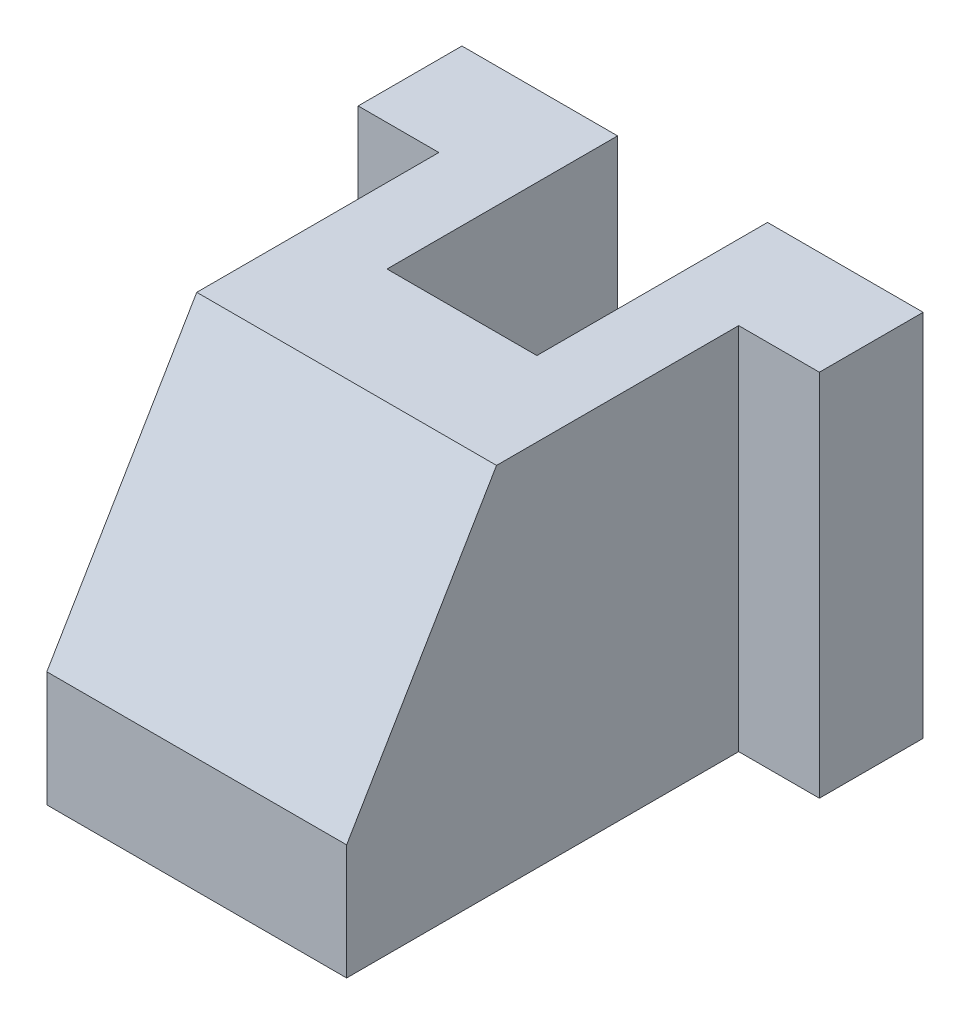
SolidWorks part; units mm, degrees
ref_plane "Front Plane" through (0, 0, 0) normal (0, 0, 1) x (1, 0, 0)
ref_plane "Top Plane" through (0, 0, 0) normal (0, 1, 0) x (1, 0, 0)
ref_plane "Right Plane" through (0, 0, 0) normal (1, 0, 0) x (0, 0, -1)
sketch "Sketch1" plane through (0, 0, 0) normal (1, 0, 0) x (0, 0, -1)
  line L0 (-43, 0) -> (0, 0)
  line L1 (0, 0) -> (0, 32)
  line L2 (0, 32) -> (-30, 32)
  line L3 (-30, 32) -> (-43, 10)
  line L4 (-43, 10) -> (-43, 0)
  dimension "D1" = 10
  dimension "D2" = 43
  dimension "D3" = 32
  dimension "D4" = 30
extrude "Boss-Extrude2" add sketch "Sketch1" against normal blind 26
sketch "Sketch2" plane through (0, 0, 0) normal (1, 0, 0) x (0, 0, -1)
  line L0 (0, 32) -> (-9, 32)
  line L1 (0, 32) -> (-30, 32) construction
  line L2 (-9, 32) -> (-9, 0)
  line L3 (-43, 0) -> (0, 0) construction
  line L4 (-9, 0) -> (0, 0)
  line L5 (0, 0) -> (0, 32)
  dimension "D1" = 9
extrude "Boss-Extrude3" add sketch "Sketch2" along normal blind 7
sketch "Sketch3" plane through (-26, 0, 0) normal (-1, 0, 0) x (0, 0, 1)
  line L0 (0, 32) -> (9, 32)
  line L1 (0, 32) -> (30, 32) construction
  line L2 (9, 32) -> (9, 0)
  line L3 (43, 0) -> (0, 0) construction
  line L4 (9, 0) -> (0, 0)
  line L5 (0, 0) -> (0, 32)
  dimension "D1" = 9
extrude "Boss-Extrude4" add sketch "Sketch3" along normal blind 7
sketch "Sketch4" plane through (0, 32, 0) normal (0, 1, 0) x (1, 0, 0)
  line L0 (-19.5, 0) -> (-6.5, 0)
  line L1 (-33, 0) -> (7, 0) construction
  line L2 (-6.5, 0) -> (-6.5, -20)
  line L3 (-6.5, -20) -> (-19.5, -20)
  line L4 (-19.5, -20) -> (-19.5, 0)
  point P4 (-20.8718, -14.9071)
  point P7 (0, 0)
  point P8 (0, 0)
  dimension "D1" = 13
  dimension "D2" = 20
  dimension "D3" = 13.5
extrude "Cut-Extrude2" cut sketch "Sketch4" against normal blind 34
sketch "Sketch7" plane through (0, 21.4211, 36.2511) normal (0, 0.5087, 0.8609) x (1, 0, 0)
  line L2 (-19, 1.1246) -> (-7, 1.1246)
  line L5 (-19, 1.1246) -> (-19, -13.2661)
  line L6 (-26, -13.2661) -> (0, -13.2661) construction
  line L7 (-19, -13.2661) -> (-7, -13.2661)
  line L8 (-7, -13.2661) -> (-7, 1.1246)
  dimension "D1" = 7
  dimension "D2" = 12
